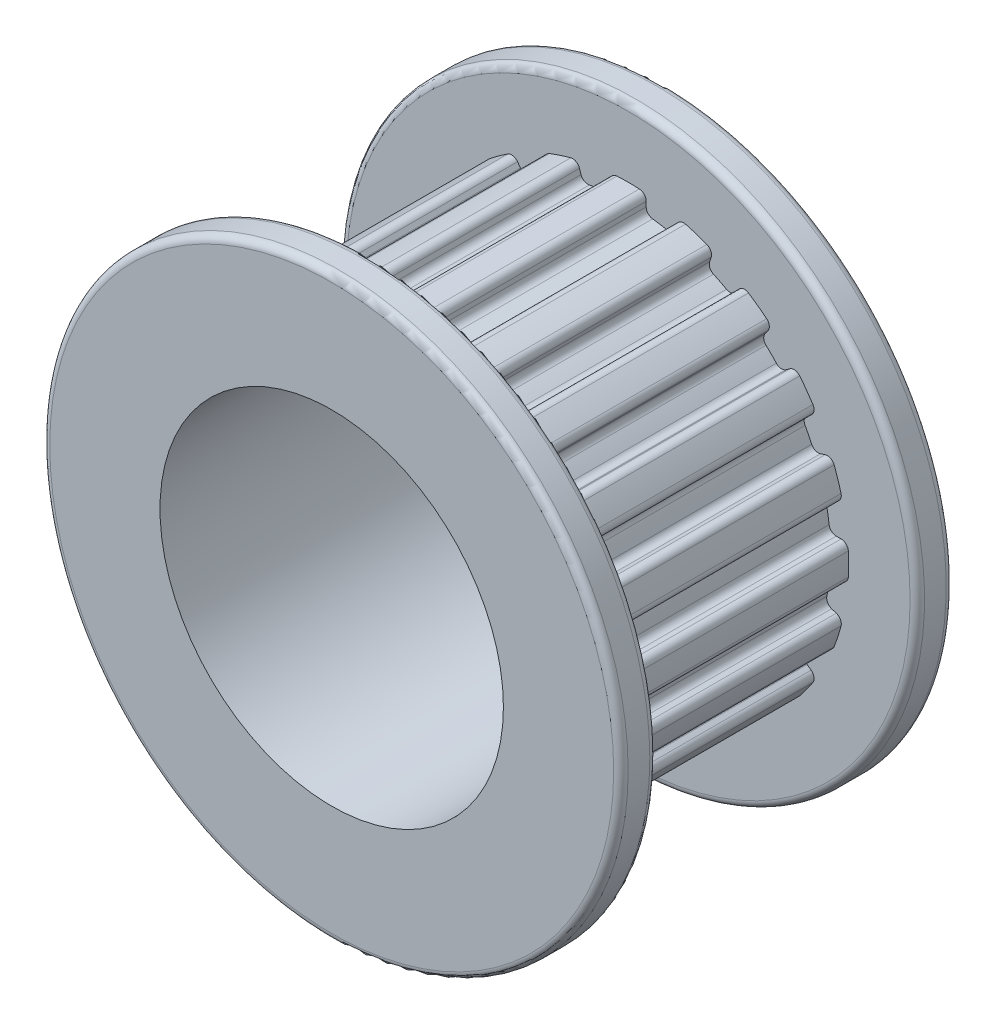
SolidWorks part; units mm, degrees
material "1060-H12 Válcovaný drát (SS)"
ref_plane "Front Plane" through (0, 0, 0) normal (0, 0, 1) x (1, 0, 0)
ref_plane "Top Plane" through (0, 0, 0) normal (0, 1, 0) x (1, 0, 0)
ref_plane "Right Plane" through (0, 0, 0) normal (1, 0, 0) x (0, 0, -1)
sketch "Skica1" plane through (0, 0, 0) normal (0, 0, 1) x (1, 0, 0)
  line L0 (0, 0) -> (0, 6.1) construction
  line L1 (0, 6.1) -> (-0.5, 6.0795) construction
  line L2 (0, 6.1) -> (0.5, 6.0795) construction
  line L3 (-0.5, 6.0795) -> (-0.5, 5.5776)
  line L4 (-0.5, 5.5776) -> (-1.2481, 5.4592) construction
  line L5 (0.5, 6.0795) -> (0.5, 5.5776)
  line L6 (1.4031, 5.9364) -> (1.2481, 5.4592)
  line L7 (2.3542, 5.6274) -> (2.1991, 5.1501)
  line L8 (3.1689, 5.2123) -> (2.8739, 4.8063)
  line L9 (3.9779, 4.6245) -> (3.683, 4.2185)
  line L10 (4.6245, 3.9779) -> (4.2185, 3.683)
  line L11 (5.2123, 3.1689) -> (4.8063, 2.8739)
  line L12 (5.6274, 2.3542) -> (5.1501, 2.1991)
  line L13 (5.9364, 1.4031) -> (5.4592, 1.2481)
  line L14 (6.0795, 0.5) -> (5.5776, 0.5)
  line L15 (6.0795, -0.5) -> (5.5776, -0.5)
  line L16 (5.9364, -1.4031) -> (5.4592, -1.2481)
  line L17 (5.6274, -2.3542) -> (5.1501, -2.1991)
  line L18 (5.2123, -3.1689) -> (4.8063, -2.8739)
  line L19 (4.6245, -3.9779) -> (4.2185, -3.683)
  line L20 (3.9779, -4.6245) -> (3.683, -4.2185)
  line L21 (3.1689, -5.2123) -> (2.8739, -4.8063)
  line L22 (2.3542, -5.6274) -> (2.1991, -5.1501)
  line L23 (1.4031, -5.9364) -> (1.2481, -5.4592)
  line L24 (0.5, -6.0795) -> (0.5, -5.5776)
  line L25 (-0.5, -6.0795) -> (-0.5, -5.5776)
  line L26 (-1.4031, -5.9364) -> (-1.2481, -5.4592)
  line L27 (-2.3542, -5.6274) -> (-2.1991, -5.1501)
  line L28 (-3.1689, -5.2123) -> (-2.8739, -4.8063)
  line L29 (-3.9779, -4.6245) -> (-3.683, -4.2185)
  line L30 (-4.6245, -3.9779) -> (-4.2185, -3.683)
  line L31 (-5.2123, -3.1689) -> (-4.8063, -2.8739)
  line L32 (-5.6274, -2.3542) -> (-5.1501, -2.1991)
  line L33 (-5.9364, -1.4031) -> (-5.4592, -1.2481)
  line L34 (-6.0795, -0.5) -> (-5.5776, -0.5)
  line L35 (-6.0795, 0.5) -> (-5.5776, 0.5)
  line L36 (-5.9364, 1.4031) -> (-5.4592, 1.2481)
  line L37 (-5.6274, 2.3542) -> (-5.1501, 2.1991)
  line L38 (-5.2123, 3.1689) -> (-4.8063, 2.8739)
  line L39 (-4.6245, 3.9779) -> (-4.2185, 3.683)
  line L40 (-3.9779, 4.6245) -> (-3.683, 4.2185)
  line L41 (-3.1689, 5.2123) -> (-2.8739, 4.8063)
  line L42 (-2.3542, 5.6274) -> (-2.1991, 5.1501)
  line L43 (-1.4031, 5.9364) -> (-1.2481, 5.4592)
  circle A0 centre (0, 0) radius 6.1 construction
  circle A1 centre (0, 0) radius 5.6 construction
  arc A2 (-1.2481, 5.4592) -> (-0.5, 5.5776) centre (0, 0) cw
  arc A3 (-0.5, 6.0795) -> (0.5, 6.0795) centre (0, 0) cw
  arc A4 (0.5, 5.5776) -> (1.2481, 5.4592) centre (0, 0) cw
  arc A5 (1.4031, 5.9364) -> (2.3542, 5.6274) centre (0, 0) cw
  arc A6 (2.1991, 5.1501) -> (2.8739, 4.8063) centre (0, 0) cw
  arc A7 (3.1689, 5.2123) -> (3.9779, 4.6245) centre (0, 0) cw
  arc A8 (3.683, 4.2185) -> (4.2185, 3.683) centre (0, 0) cw
  arc A9 (4.6245, 3.9779) -> (5.2123, 3.1689) centre (0, 0) cw
  arc A10 (4.8063, 2.8739) -> (5.1501, 2.1991) centre (0, 0) cw
  arc A11 (5.6274, 2.3542) -> (5.9364, 1.4031) centre (0, 0) cw
  arc A12 (5.4592, 1.2481) -> (5.5776, 0.5) centre (0, 0) cw
  arc A13 (6.0795, 0.5) -> (6.0795, -0.5) centre (0, 0) cw
  arc A14 (5.5776, -0.5) -> (5.4592, -1.2481) centre (0, 0) cw
  arc A15 (5.9364, -1.4031) -> (5.6274, -2.3542) centre (0, 0) cw
  arc A16 (5.1501, -2.1991) -> (4.8063, -2.8739) centre (0, 0) cw
  arc A17 (5.2123, -3.1689) -> (4.6245, -3.9779) centre (0, 0) cw
  arc A18 (4.2185, -3.683) -> (3.683, -4.2185) centre (0, 0) cw
  arc A19 (3.9779, -4.6245) -> (3.1689, -5.2123) centre (0, 0) cw
  arc A20 (2.8739, -4.8063) -> (2.1991, -5.1501) centre (0, 0) cw
  arc A21 (2.3542, -5.6274) -> (1.4031, -5.9364) centre (0, 0) cw
  arc A22 (1.2481, -5.4592) -> (0.5, -5.5776) centre (0, 0) cw
  arc A23 (0.5, -6.0795) -> (-0.5, -6.0795) centre (0, 0) cw
  arc A24 (-0.5, -5.5776) -> (-1.2481, -5.4592) centre (0, 0) cw
  arc A25 (-1.4031, -5.9364) -> (-2.3542, -5.6274) centre (0, 0) cw
  arc A26 (-2.1991, -5.1501) -> (-2.8739, -4.8063) centre (0, 0) cw
  arc A27 (-3.1689, -5.2123) -> (-3.9779, -4.6245) centre (0, 0) cw
  arc A28 (-3.683, -4.2185) -> (-4.2185, -3.683) centre (0, 0) cw
  arc A29 (-4.6245, -3.9779) -> (-5.2123, -3.1689) centre (0, 0) cw
  arc A30 (-4.8063, -2.8739) -> (-5.1501, -2.1991) centre (0, 0) cw
  arc A31 (-5.6274, -2.3542) -> (-5.9364, -1.4031) centre (0, 0) cw
  arc A32 (-5.4592, -1.2481) -> (-5.5776, -0.5) centre (0, 0) cw
  arc A33 (-6.0795, -0.5) -> (-6.0795, 0.5) centre (0, 0) cw
  arc A34 (-5.5776, 0.5) -> (-5.4592, 1.2481) centre (0, 0) cw
  arc A35 (-5.9364, 1.4031) -> (-5.6274, 2.3542) centre (0, 0) cw
  arc A36 (-5.1501, 2.1991) -> (-4.8063, 2.8739) centre (0, 0) cw
  arc A37 (-5.2123, 3.1689) -> (-4.6245, 3.9779) centre (0, 0) cw
  arc A38 (-4.2185, 3.683) -> (-3.683, 4.2185) centre (0, 0) cw
  arc A39 (-3.9779, 4.6245) -> (-3.1689, 5.2123) centre (0, 0) cw
  arc A40 (-2.8739, 4.8063) -> (-2.1991, 5.1501) centre (0, 0) cw
  arc A41 (-2.3542, 5.6274) -> (-1.4031, 5.9364) centre (0, 0) cw
  point P110 (0, 0)
  dimension "D1" = 12.2
  dimension "D2" = 0.5
  dimension "D3" = 1
  dimension "D5" = 20
extrude "Přidat vysunutím1" add sketch "Skica1" along normal blind 7.2
fillet "Zaoblit1" radius 0.2 80 edges at (-2.1991, 5.1501, 3.6) (-2.3542, 5.6274, 3.6) (-1.4031, 5.9364, 3.6) (-1.2481, 5.4592, 3.6) (-0.5, 5.5776, 3.6) (-0.5, 6.0795, 3.6) (0.5, 6.0795, 3.6) (0.5, 5.5776, 3.6) (1.2481, 5.4592, 3.6) (1.4031, 5.9364, 3.6) (2.3542, 5.6274, 3.6) (2.1991, 5.1501, 3.6) (-2.8739, 4.8063, 3.6) (-3.1689, 5.2123, 3.6) (-3.9779, 4.6245, 3.6) (-3.683, 4.2185, 3.6) (-4.2185, 3.683, 3.6) (-4.6245, 3.9779, 3.6) (-5.2123, 3.1689, 3.6) (-4.8063, 2.8739, 3.6) (-5.1501, 2.1991, 3.6) (-5.6274, 2.3542, 3.6) (-5.9364, 1.4031, 3.6) (-5.4592, 1.2481, 3.6) (-5.5776, 0.5, 3.6) (-6.0795, 0.5, 3.6) (-6.0795, -0.5, 3.6) (-5.5776, -0.5, 3.6) (-5.4592, -1.2481, 3.6) (-5.9364, -1.4031, 3.6) (-5.6274, -2.3542, 3.6) (-5.1501, -2.1991, 3.6) (-4.8063, -2.8739, 3.6) (-5.2123, -3.1689, 3.6) (-4.6245, -3.9779, 3.6) (-4.2185, -3.683, 3.6) (-3.683, -4.2185, 3.6) (-3.9779, -4.6245, 3.6) (-3.1689, -5.2123, 3.6) (-2.8739, -4.8063, 3.6) (-2.1991, -5.1501, 3.6) (-2.3542, -5.6274, 3.6) (-1.4031, -5.9364, 3.6) (-1.2481, -5.4592, 3.6) (-0.5, -5.5776, 3.6) (-0.5, -6.0795, 3.6) (0.5, -6.0795, 3.6) (0.5, -5.5776, 3.6) (1.2481, -5.4592, 3.6) (1.4031, -5.9364, 3.6) (2.3542, -5.6274, 3.6) (2.1991, -5.1501, 3.6) (2.8739, -4.8063, 3.6) (3.1689, -5.2123, 3.6) (3.9779, -4.6245, 3.6) (3.683, -4.2185, 3.6) (4.2185, -3.683, 3.6) (4.6245, -3.9779, 3.6) (5.2123, -3.1689, 3.6) (4.8063, -2.8739, 3.6) (5.1501, -2.1991, 3.6) (5.6274, -2.3542, 3.6) (5.9364, -1.4031, 3.6) (5.4592, -1.2481, 3.6) (5.5776, -0.5, 3.6) (6.0795, -0.5, 3.6) (6.0795, 0.5, 3.6) (5.5776, 0.5, 3.6) (5.4592, 1.2481, 3.6) (5.9364, 1.4031, 3.6) (5.6274, 2.3542, 3.6) (5.1501, 2.1991, 3.6) (4.8063, 2.8739, 3.6) (5.2123, 3.1689, 3.6) (4.6245, 3.9779, 3.6) (4.2185, 3.683, 3.6) (3.683, 4.2185, 3.6) (3.9779, 4.6245, 3.6) (2.8739, 4.8063, 3.6) (3.1689, 5.2123, 3.6)
sketch "Esboço1" plane through (0, 0, 7.2) normal (0, 0, 1) x (1, 0, 0)
  circle A0 centre (0, 0) radius 8
sketch "Esboço2" plane through (0, 0, 0) normal (0, 0, -1) x (-1, 0, 0)
  circle A0 centre (0, 0) radius 8
  dimension "D1" = 16
extrude "Ressalto-extrusão1" add sketch "Esboço1" along normal blind 1
extrude "Ressalto-extrusão2" add sketch "Esboço2" along normal blind 1
fillet "Filete3" radius 0.2 2 edges at (8, 0, 7.2) (8, 0, 8.2)
fillet "Filete4" radius 0.2 2 edges at (-8, 0, 0) (-8, 0, -1)
sketch "Esboço3" plane through (0, 0, 8.2) normal (0, 0, 1) x (1, 0, 0)
  circle A0 centre (0, 0) radius 4.75
  dimension "D1" = 9.5
extrude "Corte-extrusão1" cut sketch "Esboço3" against normal blind 9.2
